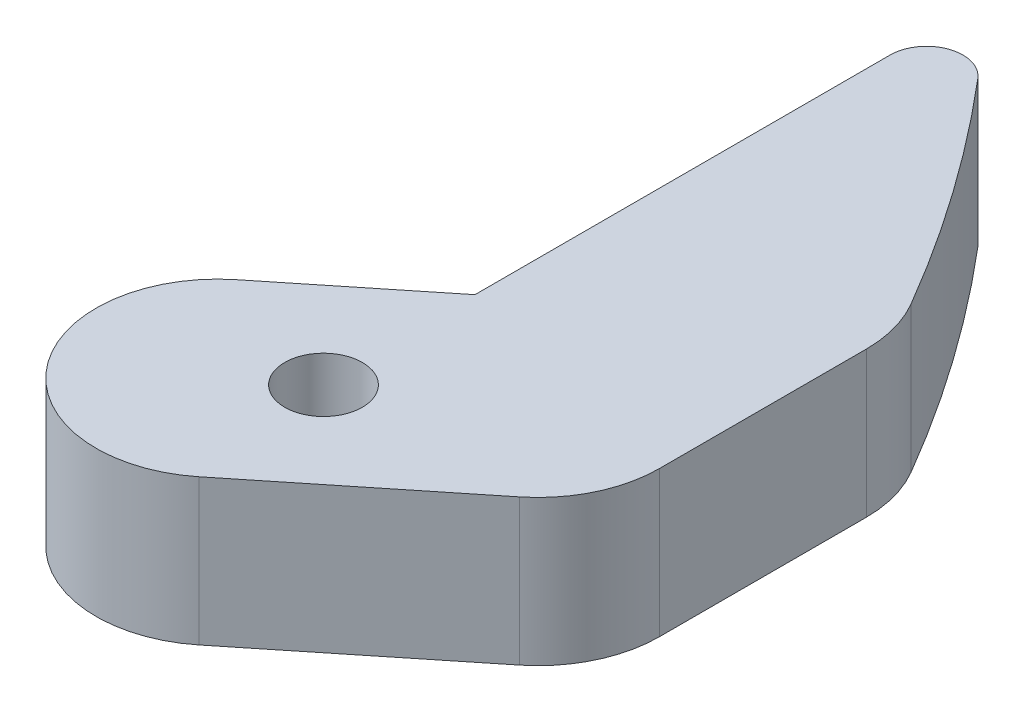
SolidWorks part; units mm, degrees
material "MDF"
ref_plane "Plano frontal" through (0, 0, 0) normal (0, 0, 1) x (1, 0, 0)
ref_plane "Plano superior" through (0, 0, 0) normal (0, 1, 0) x (1, 0, 0)
ref_plane "Plano direito" through (0, 0, 0) normal (1, 0, 0) x (0, 0, -1)
ref_plane "Plano1" through (0, -12, 0) normal (0, -1, 0) x (1, 0, 0)
sketch "Esboço1" plane through (0, -12, 0) normal (0, -1, 0) x (1, 0, 0)
  line L0 (-5.5544, -1.9504) -> (-0.0984, -6.3359)
  line L1 (-0.0984, -6.3359) -> (-0.0984, -23.4342)
  line L2 (9.9016, -12.4543) -> (9.9016, -3.9398)
  line L3 (8.034, -0.0427) -> (0.7105, 5.8439)
  line L4 (0, 0) -> (-28.7366, 23.0979) construction
  line L5 (-3.1324, -3.8971) -> (3.1324, 3.8971) construction
  arc A0 (0.7105, 5.8439) -> (-5.5544, -1.9504) centre (-2.422, 1.9467) ccw
  arc A1 (-0.0984, -23.4342) -> (2.5451, -24.405) centre (1.4016, -23.4342) ccw
  arc A2 (2.5451, -24.405) -> (9.2207, -14.9732) centre (-47.5984, 18.1641) ccw
  arc A3 (9.2207, -14.9732) -> (9.9016, -12.4543) centre (4.9016, -12.4543) ccw
  arc A4 (9.9016, -3.9398) -> (8.034, -0.0427) centre (4.9016, -3.9398) ccw
  circle A5 centre (0, 0) radius 1.6
  dimension "D1" = 3.2
  dimension "D3" = 1.5
  dimension "D7" = 23.4342
  dimension "D8" = 65.7761
  dimension "D2" = 10
  dimension "D4" = 10
  dimension "D5" = 6.2887
  dimension "D6" = 3.1073
  dimension "D9" = 6.3359
  dimension "D10" = 12.4543
extrude "Ressalto-extrusão1" add sketch "Esboço1" against normal blind 6
